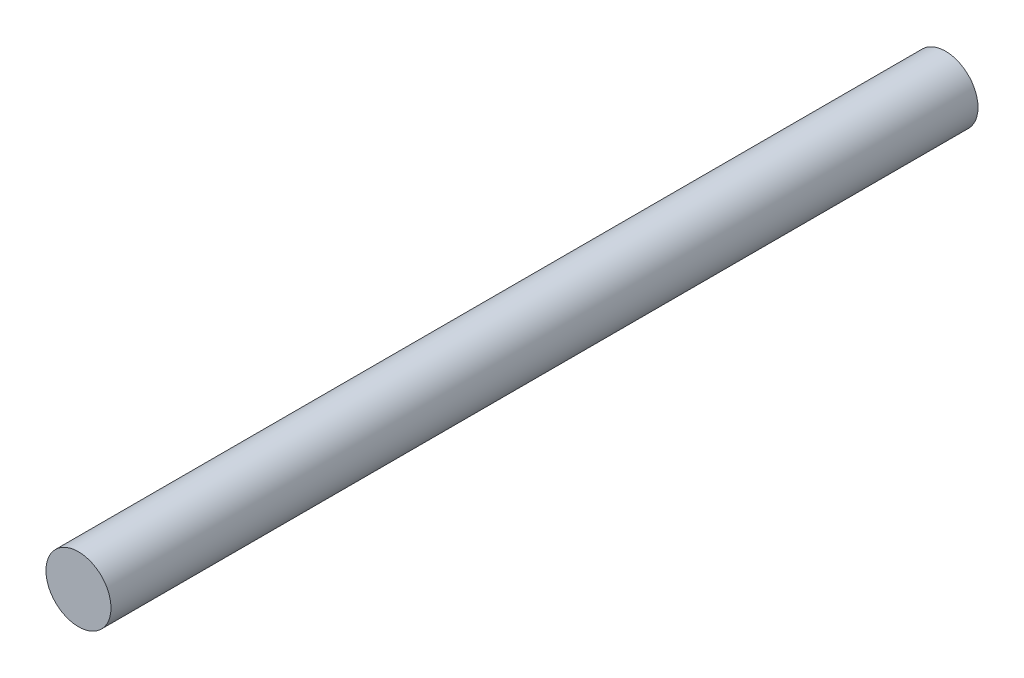
SolidWorks part; units mm, degrees
ref_plane "Front Plane" through (0, 0, 0) normal (0, 0, 1) x (1, 0, 0)
ref_plane "Top Plane" through (0, 0, 0) normal (0, 1, 0) x (1, 0, 0)
ref_plane "Right Plane" through (0, 0, 0) normal (1, 0, 0) x (0, 0, -1)
sketch "Sketch1" plane through (0, 0, 0) normal (0, 0, 1) x (1, 0, 0)
  circle A0 centre (0, 0) radius 3
extrude "Boss-Extrude1" add sketch "Sketch1" along normal blind 80
